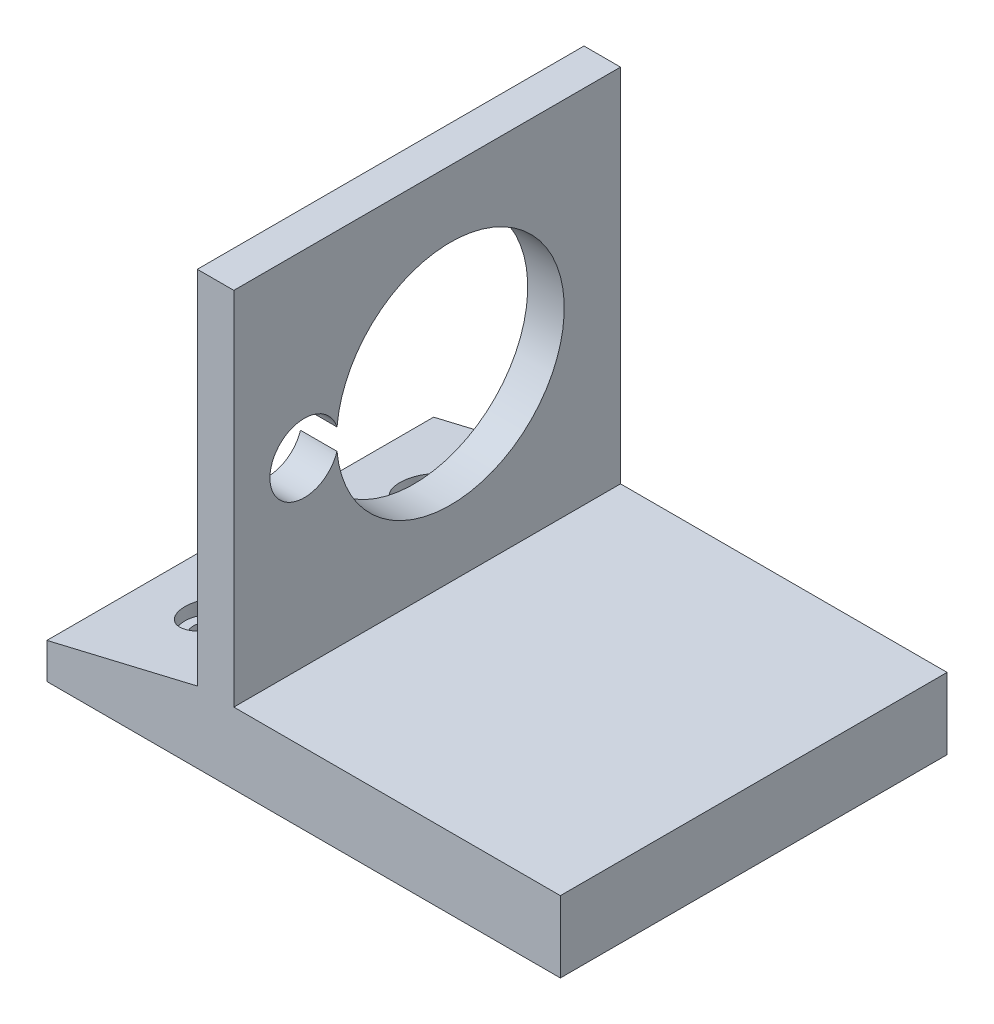
SolidWorks part; units mm, degrees
ref_plane "Plan de face" through (0, 0, 0) normal (0, 0, 1) x (1, 0, 0)
ref_plane "Plan de dessus" through (0, 0, 0) normal (0, 1, 0) x (1, 0, 0)
ref_plane "Plan de droite" through (0, 0, 0) normal (1, 0, 0) x (0, 0, -1)
sketch "Esquisse1" plane through (0, 0, 0) normal (0, 0, 1) x (1, 0, 0)
  line L0 (-38, -554.7609) -> (-38, -596.7609)
  line L1 (-38, -596.7609) -> (0, -596.7609)
  line L2 (0, -596.7609) -> (0, -605.0609)
  line L3 (0, -605.0609) -> (-59.749, -605.0609)
  line L4 (-400, -605.0609) -> (0, -605.0609) construction
  line L5 (-59.749, -605.0609) -> (-59.749, -600.9109)
  line L6 (-59.749, -600.9109) -> (-42.2498, -596.7609)
  line L7 (-42.2498, -596.7609) -> (-42.2498, -554.7609)
  line L8 (-42.2498, -554.7609) -> (-38, -554.7609)
extrude "Boss.-Extru.1" add sketch "Esquisse1" against normal up to surface (45 mm away)
sketch "Esquisse2" plane through (-42.2498, 0, 0) normal (-1, 0, 0) x (0, 0, 1)
  circle A0 centre (-8.2, -575.7609) radius 4 construction
  arc A1 (-12.007, -576.9884) -> (-12.007, -574.5333) centre (-8.2, -575.7609) ccw
  circle A4 centre (-25.2, -575.7609) radius 13.25
  arc A5 (-12.007, -574.5333) -> (-12.007, -576.9884) centre (-25.2, -575.7609) ccw
  dimension "D1" = 1
extrude "Enlèv. mat.-Extru.1" cut sketch "Esquisse2" against normal through all
sketch "Esquisse3" plane through (0, -605.0609, 0) normal (0, -1, 0) x (1, 0, 0)
  line L0 (0, 0) -> (-400, 0) construction
  line L1 (0, -45) -> (-400, -45) construction
  circle A0 centre (-50.6835, -35) radius 2
  circle A1 centre (-50.6835, -10) radius 2
  dimension "D3" = 4
  dimension "D1" = 10
  dimension "D2" = 10
extrude "Enlèv. mat.-Extru.2" cut sketch "Esquisse3" against normal through all
sketch "Esquisse4" plane through (0, -554.7609, 0) normal (0, 1, 0) x (1, 0, 0)
  circle A5 centre (-50.6835, 10) radius 3
  circle A6 centre (-50.6835, 10) radius 3
  circle A8 centre (-50.6835, 35) radius 3
  circle A9 centre (-50.6835, 35) radius 3
  dimension "D1" = 1
  dimension "D2" = 1
extrude "Enlèv. mat.-Extru.3" cut sketch "Esquisse4" against normal up to vertex (46.15 mm away)
